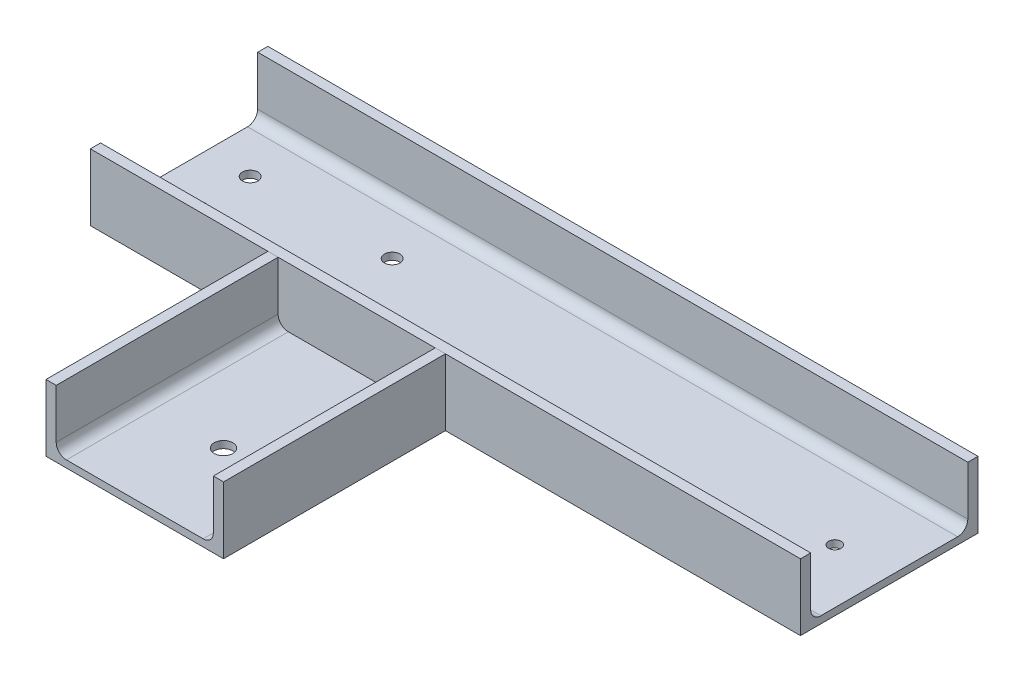
SolidWorks part; units mm, degrees
other "DetailItem3"
other "Weld Folder"
other "Weld Bead3"
ref_plane "Front Plane" through (0, 0, 0) normal (0, 0, 1) x (1, 0, 0)
ref_plane "Top Plane" through (0, 0, 0) normal (0, 1, 0) x (1, 0, 0)
ref_plane "Right Plane" through (0, 0, 0) normal (1, 0, 0) x (0, 0, -1)
sketch "Sketch1" plane through (0, 0, 0) normal (0, 1, 0) x (1, 0, 0)
  line L0 (400, 0) -> (-400, 0)
  line L1 (-100, 0) -> (-100, -250)
  point P4 (0, 0)
  dimension "D1" = 800
  dimension "D2" = 250
  dimension "D3" = 500
other "Square hss AL CS CHANNEL SQR END 4 X 2.02(1)"
ref_plane "Plane2" through (400, 0, 0) normal (-1, 0, 0) x (0, 1, 0)
sketch "Sketch157" plane through (400, 0, 0) normal (-1, 0, 0) x (0, 1, 0)
  line L0 (0, 0) -> (0, 200)
  line L1 (0, 100) -> (8, 100) construction
  line L2 (8, 177) -> (8, 23)
  line L3 (19.5, 11.5) -> (75, 11.5)
  line L5 (75, 0) -> (0, 0)
  line L6 (75, 200) -> (0, 200)
  line L7 (75, 0) -> (75, 11.5)
  line L8 (75, 200) -> (75, 188.5)
  line L9 (19.5, 188.5) -> (75, 188.5)
  arc A0 (8, 177) -> (19.5, 188.5) centre (19.5, 177) cw
  arc A2 (19.5, 11.5) -> (8, 23) centre (19.5, 23) cw
  point P2 (4, 100)
  point P5 (0, 0)
  point P15 (37.5, 200)
  point P17 (37.5, 0)
  dimension "Radius_1" = 11.5
  dimension "Thickness" = 11.5
  dimension "H_Leg" = 75
  dimension "tw" = 8
  dimension "V_Leg" = 200
other "Square hss AL CS CHANNEL SQR END 4 X 2.02(2)"
ref_plane "Plane3" through (0, 0, 0) normal (0, 0, 1) x (0, 1, 0)
sketch "Sketch158" plane through (0, 0, 0) normal (0, 0, 1) x (0, 1, 0)
  line L0 (0, 0) -> (0, 200)
  line L1 (0, 100) -> (8, 100) construction
  line L2 (8, 177) -> (8, 23)
  line L3 (19.5, 11.5) -> (75, 11.5)
  line L5 (75, 0) -> (0, 0)
  line L6 (75, 200) -> (0, 200)
  line L7 (75, 0) -> (75, 11.5)
  line L8 (75, 200) -> (75, 188.5)
  line L9 (19.5, 188.5) -> (75, 188.5)
  arc A0 (8, 177) -> (19.5, 188.5) centre (19.5, 177) cw
  arc A2 (19.5, 11.5) -> (8, 23) centre (19.5, 23) cw
  point P2 (4, 100)
  point P5 (0, 0)
  point P15 (37.5, 200)
  point P17 (37.5, 0)
  dimension "Radius_1" = 11.5
  dimension "Thickness" = 11.5
  dimension "H_Leg" = 75
  dimension "tw" = 8
  dimension "V_Leg" = 200
sketch "Sketch159" plane through (0, 0, 0) normal (0, 0, 1) x (1, 0, 0)
  line L0 (-11.5, 75) -> (-11.5, 19.5) construction
  line L1 (-23, 8) -> (-177, 8) construction
  line L2 (-188.5, 19.5) -> (-188.5, 75) construction
  line L3 (-11.5, 75) -> (-11.5, 19.5)
  line L4 (-23, 8) -> (-177, 8)
  line L5 (-188.5, 19.5) -> (-188.5, 75)
  line L6 (-188.5, 75) -> (-200, 75) construction
  line L7 (-200, 75) -> (-200, 0) construction
  line L8 (-200, 0) -> (0, 0) construction
  line L9 (0, 0) -> (0, 75) construction
  line L10 (0, 75) -> (-11.5, 75) construction
  line L11 (-188.5, 75) -> (-200, 75)
  line L12 (-200, 75) -> (-200, 0)
  line L13 (-200, 0) -> (0, 0)
  line L14 (0, 0) -> (0, 75)
  line L15 (0, 75) -> (-11.5, 75)
  arc A0 (-23, 8) -> (-11.5, 19.5) centre (-23, 19.5) ccw construction
  arc A1 (-188.5, 19.5) -> (-177, 8) centre (-177, 19.5) ccw construction
  arc A2 (-23, 8) -> (-11.5, 19.5) centre (-23, 19.5) ccw
  arc A3 (-188.5, 19.5) -> (-177, 8) centre (-177, 19.5) ccw
sketch "Sketch160" plane through (0, 8, 0) normal (0, 1, 0) x (1, 0, 0)
  line L1 (-400, 200) -> (-300, 200) construction
  line L2 (-400, 200) -> (-400, 0) construction
  line L3 (-400, 0) -> (-300, 0) construction
  line L6 (-400, 200) -> (400, 200) construction
  line L7 (400, 0) -> (-400, 0) construction
  line L10 (-400, 23) -> (-400, 177) construction
sketch "Sketch163" plane through (0, 8, 0) normal (0, 1, 0) x (1, 0, 0)
  line L0 (-100, 0) -> (-100, -250) construction
  line L1 (-23, -250) -> (-177, -250) construction
  point P0 (-100, -210)
  dimension "D1" = 40
hole_wizard "M24x3.0 Tapped Hole1" positions "Sketch164" profile "Sketch165" tap size "M24x3.0" standard "ANSI Metric"
sketch "Sketch164" plane through (0, 8, 0) normal (0, 1, 0) x (1, 0, 0)
  line L1 (-400, 0) -> (400, 0) construction
  point P0 (-100, -150)
  point P5 (0, 0)
  dimension "D1" = 150
sketch "Sketch165" plane through (-100, 8, 150) normal (1, 0, 0) x (0, 0, 1)
  line L0 (0, 0) -> (0, 63.309)
  line L1 (0, 63.309) -> (10.5, 57)
  line L2 (10.5, 57) -> (10.5, 0)
  line L5 (10.5, 0) -> (0, 0)
  line L10 (0, 63.309) -> (-10.5, 57) construction
  line L11 (0, -6.35) -> (0, 107.95) construction
  dimension "Tap Drill Dia." = 21
  dimension "Tap Drill Depth" = 57
  dimension "Drill Angle" = 118
sketch "Sketch166" plane through (0, 8, 0) normal (0, 1, 0) x (1, 0, 0)
  line L0 (-400, 200) -> (400, 200) construction
  line L1 (400, 0) -> (400, 200) construction
  point P0 (343.91, 124.8)
  dimension "D1" = 75.2
  dimension "D2" = 56.09
hole_wizard "M16x2.0 Tapped Hole1" positions "Sketch167" profile "Sketch168" tap size "M16x2.0" standard "ANSI Metric" end condition through all
sketch "Sketch167" plane through (0, 8, 0) normal (0, 1, 0) x (1, 0, 0)
  line L0 (338.672, 100) -> (400, 100) construction
  line L1 (400, 23) -> (400, 177) construction
  point P0 (338.672, 100)
sketch "Sketch168" plane through (338.672, 8, -100) normal (1, 0, 0) x (0, 0, 1)
  line L0 (0, 0) -> (0, 8)
  line L1 (0, 8) -> (7, 8)
  line L2 (7, 8) -> (7, 0)
  line L5 (7, 0) -> (0, 0)
  line L11 (0, -6.35) -> (0, 107.95) construction
  dimension "Thru Tap Drill Dia." = 14
  dimension "Thru Tap Drill Depth" = 8
sketch "Sketch169" plane through (0, 8, 0) normal (0, 1, 0) x (1, 0, 0)
  line L0 (-400, 23) -> (-400, 177) construction
  line L1 (-350, 130) -> (-190, 130)
  line L2 (-350, 130) -> (-350, 70)
  line L3 (-350, 70) -> (-190, 70)
  line L4 (-190, 130) -> (-190, 70)
  line L5 (-400, 100) -> (-350, 100) construction
  dimension "D1" = 50
  dimension "D2" = 160
  dimension "D3" = 60
hole_wizard "M20x2.5 Tapped Hole1" positions "Sketch170" profile "Sketch171" tap size "M20x2.5" standard "ANSI Metric"
sketch "Sketch170" plane through (0, 8, 0) normal (0, 1, 0) x (1, 0, 0)
  point P0 (-350, 130)
  point P3 (-190, 130)
  point P6 (-190, 70)
  point P9 (-350, 70)
sketch "Sketch171" plane through (-350, 8, -130) normal (1, 0, 0) x (0, 0, 1)
  line L0 (0, 0) -> (0, 52.7575)
  line L1 (0, 52.7575) -> (8.75, 47.5)
  line L2 (8.75, 47.5) -> (8.75, 0)
  line L5 (8.75, 0) -> (0, 0)
  line L10 (0, 52.7575) -> (-8.75, 47.5) construction
  line L11 (0, -6.35) -> (0, 107.95) construction
  dimension "Tap Drill Dia." = 17.5
  dimension "Tap Drill Depth" = 47.5
  dimension "Drill Angle" = 118
